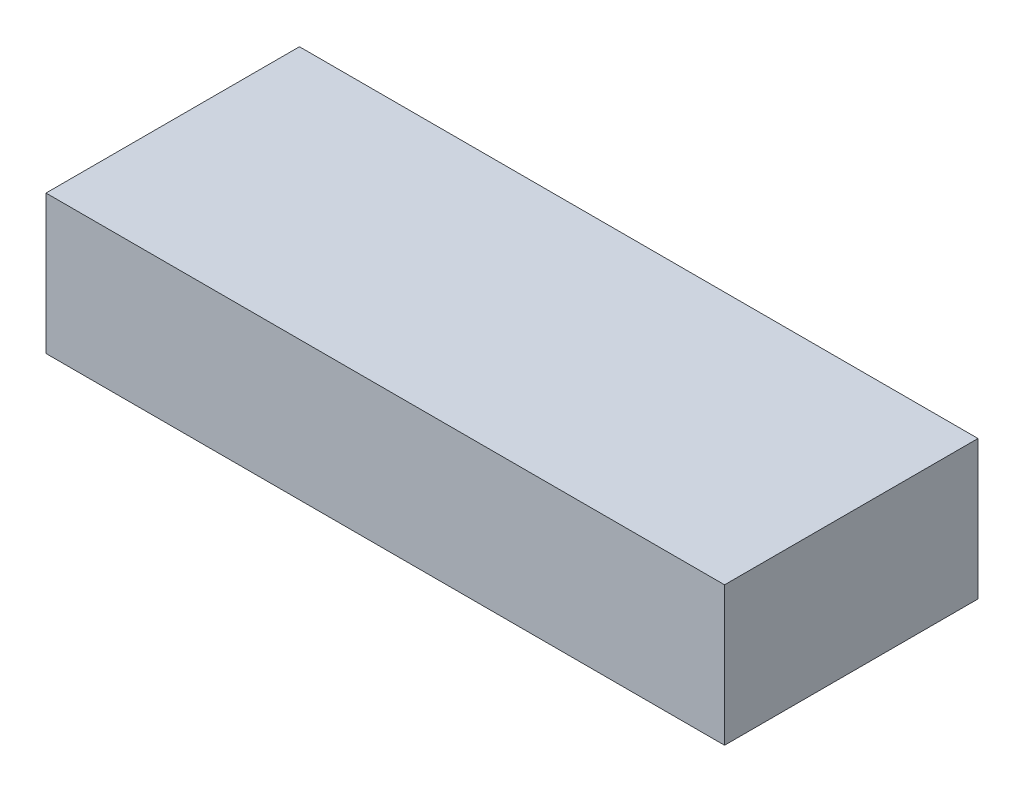
SolidWorks part; units mm, degrees
ref_plane "Front Plane" through (0, 0, 0) normal (0, 0, 1) x (1, 0, 0)
ref_plane "Top Plane" through (0, 0, 0) normal (0, 1, 0) x (1, 0, 0)
ref_plane "Right Plane" through (0, 0, 0) normal (1, 0, 0) x (0, 0, -1)
sketch "Sketch1" plane through (0, 0, 0) normal (0, 0, 1) x (1, 0, 0)
  line L0 (0, 0) -> (83, 0)
  line L1 (83, 0) -> (83, 17)
  line L2 (83, 17) -> (0, 17)
  line L3 (0, 17) -> (0, 0)
  dimension "D1" = 83
  dimension "D2" = 17
extrude "Boss-Extrude1" add sketch "Sketch1" along normal blind 31
